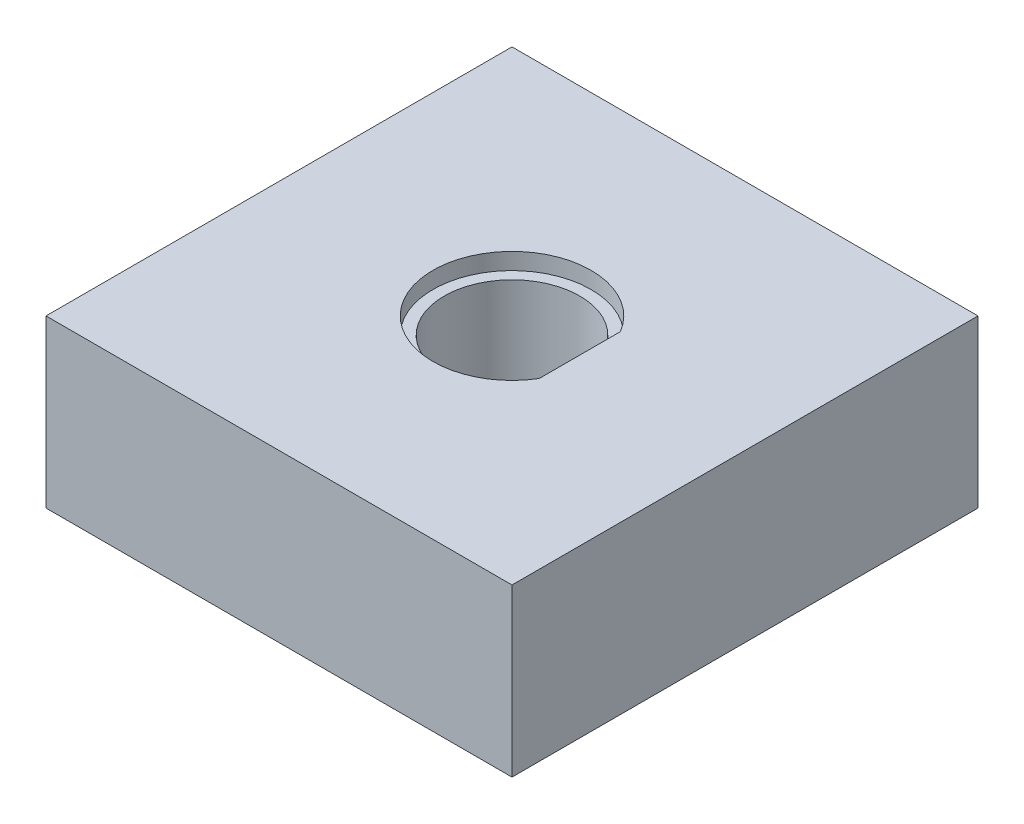
SolidWorks part; units mm, degrees
ref_plane "Front Plane" through (0, 0, 0) normal (0, 0, 1) x (1, 0, 0)
ref_plane "Top Plane" through (0, 0, 0) normal (0, 1, 0) x (1, 0, 0)
ref_plane "Right Plane" through (0, 0, 0) normal (1, 0, 0) x (0, 0, -1)
sketch "Sketch1" plane through (0, 0, 0) normal (0, 1, 0) x (1, 0, 0)
  line L1 (-14, -14) -> (14, -14)
  line L2 (-14, -14) -> (-14, 14)
  line L3 (-14, 14) -> (14, 14)
  line L4 (14, -14) -> (14, 14)
  line L5 (-14, -14) -> (14, 14) construction
  line L6 (-14, 14) -> (14, -14) construction
  point P0 (0, 0)
  dimension "D1" = 28
  dimension "D2" = 28
extrude "Boss-Extrude1" add sketch "Sketch1" along normal blind 10
sketch "Sketch2" plane through (0, 10, 0) normal (0, 1, 0) x (1, 0, 0)
  circle A0 centre (0, 0) radius 4.075
  dimension "D1" = 8.15
extrude "Cut-Extrude1" cut sketch "Sketch2" against normal through all
sketch "Sketch3" plane through (0, 10, 0) normal (0, 1, 0) x (1, 0, 0)
  line L0 (4.075, -2.4407) -> (4.075, 2.4407)
  circle A0 centre (0, 0) radius 4.075 construction
  arc A1 (4.075, 2.4407) -> (4.075, -2.4407) centre (0, 0) ccw
  point P0 (4.0328, 2.1026)
  point P7 (0, 0)
  dimension "D1" = 4.75
extrude "Cut-Extrude2" cut sketch "Sketch3" against normal blind 1
